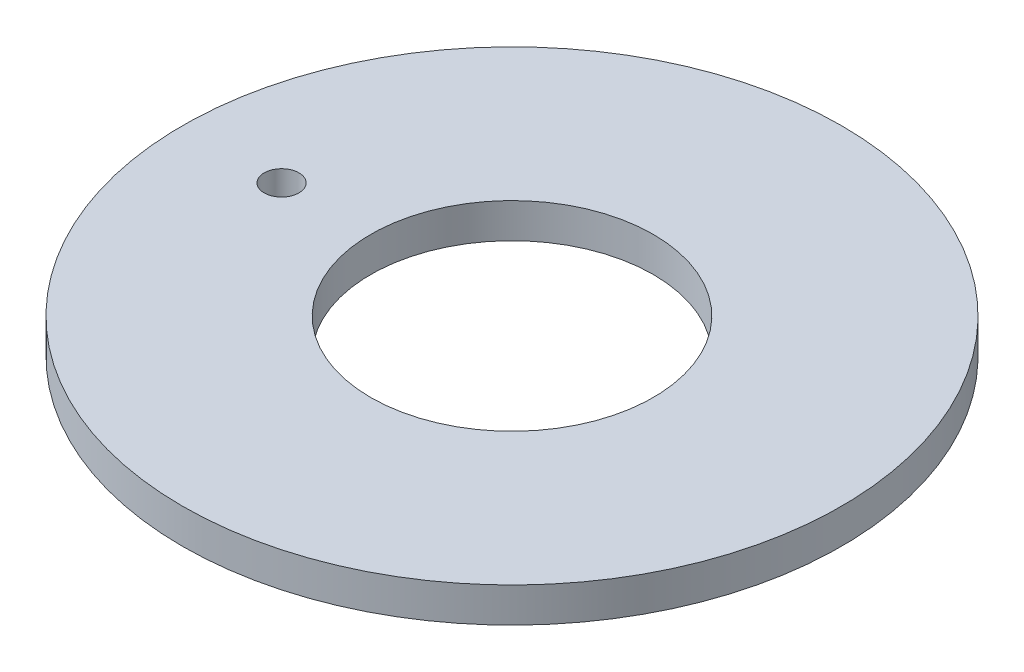
SolidWorks part; units mm, degrees
ref_plane "Front Plane" through (0, 0, 0) normal (0, 0, 1) x (1, 0, 0)
ref_plane "Top Plane" through (0, 0, 0) normal (0, 1, 0) x (1, 0, 0)
ref_plane "Right Plane" through (0, 0, 0) normal (1, 0, 0) x (0, 0, -1)
sketch "Sketch1" plane through (0, 0, 0) normal (0, 1, 0) x (1, 0, 0)
  circle A0 centre (0, 0) radius 37.9
  circle A1 centre (0, 0) radius 16.25
  dimension "D1" = 32.5
  dimension "D2" = 75.8
extrude "Boss-Extrude1" add sketch "Sketch1" along normal blind 4
sketch "Sketch2" plane through (0, 4, 0) normal (0, 1, 0) x (1, 0, 0)
  circle A0 centre (0, 0) radius 26.5 construction
  circle A1 centre (-26.5, 0) radius 2
  circle A2 centre (0, 0) radius 16.25 construction
  circle A3 centre (0, 0) radius 37.9 construction
  point P5 (-28.5, 0)
  point P6 (-24.5, 0)
  point P7 (-16.25, 0)
  point P8 (-37.9, 0)
  dimension "D1" = 53
  dimension "D2" = 4
extrude "Cut-Extrude1" cut sketch "Sketch2" against normal through all
